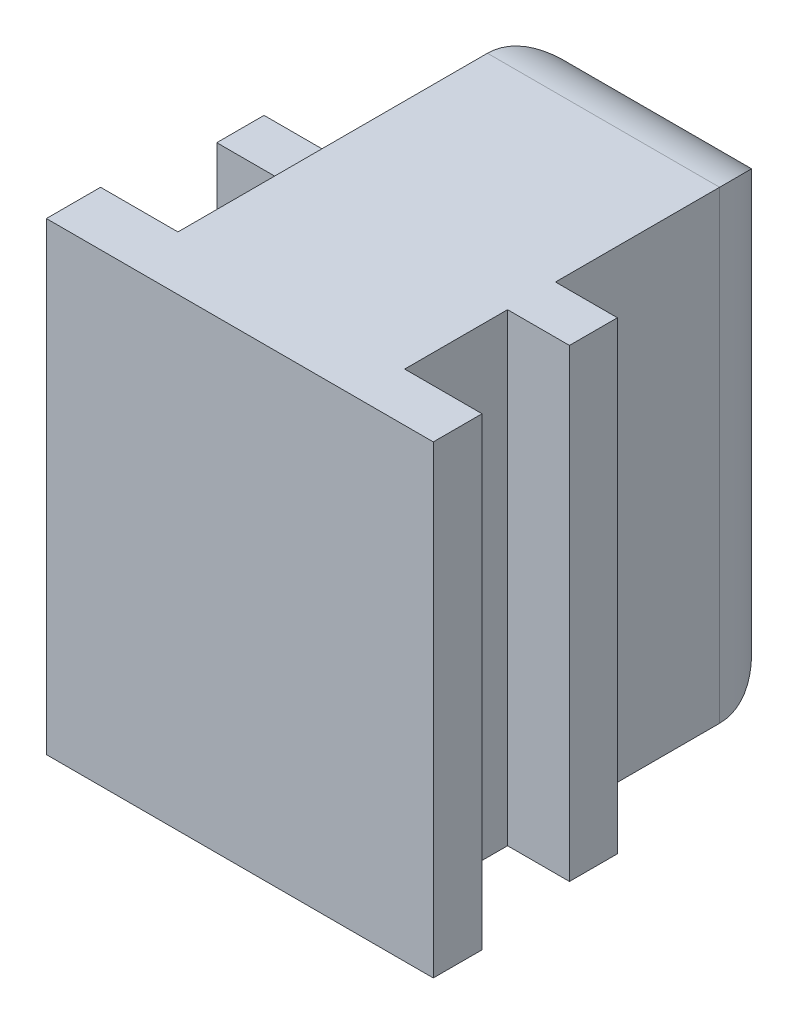
SolidWorks part; units mm, degrees
ref_plane "前视基准面" through (0, 0, 0) normal (0, 0, 1) x (1, 0, 0)
ref_plane "上视基准面" through (0, 0, 0) normal (0, 1, 0) x (1, 0, 0)
ref_plane "右视基准面" through (0, 0, 0) normal (1, 0, 0) x (0, 0, -1)
other "Configuration Table"
sketch "草图3" plane through (0, 0, 0) normal (0, 0, 1) x (1, 0, 0)
  line L1 (-2.0385, 1.183) -> (0.9615, 1.183)
  line L2 (-2.0385, 1.183) -> (-2.0385, -4.817)
  line L3 (-2.0385, -4.817) -> (0.9615, -4.817)
  line L4 (0.9615, 1.183) -> (0.9615, -4.817)
  dimension "D1" = 3
  dimension "D2" = 6
extrude "凸台-拉伸2" add sketch "草图3" along normal blind 3.5
sketch "草图4" plane through (0, 0, 3.5) normal (0, 0, 1) x (1, 0, 0)
  line L1 (-1.2395, -0.1964) -> (0.1779, -0.1964)
  line L2 (-1.2395, -0.1964) -> (-1.2395, -3.2769)
  line L3 (-1.2395, -3.2769) -> (0.1779, -3.2769)
  line L4 (0.1779, -0.1964) -> (0.1779, -3.2769)
extrude "切除-拉伸1" cut sketch "草图4" against normal blind 0.8 flip side to cut
sketch "草图9" plane through (0, 0, 0) normal (0, 0, -1) x (-1, 0, 0)
  line L5 (-0.9615, 1.183) -> (2.0385, 1.183)
  line L6 (-0.9615, 1.183) -> (-0.9615, -4.817)
  line L7 (-0.9615, -4.817) -> (2.0385, -4.817)
  line L8 (2.0385, 1.183) -> (2.0385, -4.817)
extrude "凸台-拉伸5" add sketch "草图9" along normal blind 1.5
fillet "圆角2" radius 1 4 edges at (-0.5385, 1.183, -1.5) (-0.5385, -4.817, -1.5) (-2.0385, -1.817, -1.5) (0.9615, -1.817, -1.5)
ref_plane "基准面1" through (-2.0385, 1.183, -0.5) normal (0, 0, -1) x (-1, 0, 0)
sketch "草图6" plane through (-2.0385, 0, 0) normal (-1, 0, 0) x (0, 0, 1)
  line L0 (2.7, -4.817) -> (-0.5, -4.817) construction
  line L1 (1.587, 1.1312) -> (2.1982, 1.1312)
  line L2 (1.587, 1.1312) -> (1.587, -4.817)
  line L3 (1.587, -4.817) -> (2.1982, -4.817)
  line L4 (2.1982, 1.1312) -> (2.1982, -4.817)
extrude "凸台-拉伸3" add sketch "草图6" along normal blind 0.8
sketch "草图8" plane through (0.9615, 0, 0) normal (1, 0, 0) x (0, 0, -1)
  line L0 (-2.7, 1.183) -> (0.5, 1.183) construction
  line L1 (-2.2402, 1.183) -> (-1.621, 1.183)
  line L2 (-2.2402, 1.183) -> (-2.2402, -4.817)
  line L3 (-2.2402, -4.817) -> (-1.621, -4.817)
  line L4 (-1.621, 1.183) -> (-1.621, -4.817)
  line L5 (-2.7, -4.817) -> (0.5, -4.817) construction
extrude "凸台-拉伸4" add sketch "草图8" along normal blind 0.8
sketch "草图10" plane through (0, 0, 3.5) normal (0, 0, 1) x (1, 0, 0)
  line L1 (-2.0806, 1.0827) -> (0.8643, 1.0827)
  line L2 (-2.0806, 1.0827) -> (-2.0806, -4.852)
  line L3 (-2.0806, -4.852) -> (0.8643, -4.852)
  line L4 (0.8643, 1.0827) -> (0.8643, -4.852)
extrude "凸台-拉伸6" add sketch "草图10" against normal blind 2
sketch "草图11" plane through (0, 0, 2.7) normal (0, 0, 1) x (1, 0, 0)
  line L2 (-2.0385, 1.183) -> (0.9615, 1.183)
  line L3 (-2.0385, 1.183) -> (-2.0385, -4.817)
  line L4 (-2.0385, -4.817) -> (0.9615, -4.817)
  line L5 (0.9615, 1.183) -> (0.9615, -4.817)
extrude "凸台-拉伸7" add sketch "草图11" along normal blind 1.5
sketch "草图12" plane through (-2.0385, 0, 0) normal (-1, 0, 0) x (0, 0, 1)
  line L0 (3.5, -4.817) -> (3.5, 1.0827) construction
  line L1 (4.2, 1.183) -> (3.5, 1.183)
  line L2 (4.2, 1.183) -> (4.2, -4.817)
  line L3 (4.2, -4.817) -> (3.5, -4.817)
  line L4 (3.5, 1.183) -> (3.5, -4.817)
extrude "凸台-拉伸8" add sketch "草图12" along normal blind 1.5
sketch "草图13" plane through (0.9615, 0, 0) normal (1, 0, 0) x (0, 0, -1)
  line L0 (-4.2, -4.817) -> (-2.2402, -4.817) construction
  line L1 (-4.2, 1.183) -> (-3.5697, 1.183)
  line L2 (-4.2, 1.183) -> (-4.2, -4.817)
  line L3 (-4.2, -4.817) -> (-3.5697, -4.817)
  line L4 (-3.5697, 1.183) -> (-3.5697, -4.817)
extrude "凸台-拉伸9" add sketch "草图13" along normal blind 1.5
sketch "草图14" plane through (2.4615, 0, 0) normal (1, 0, 0) x (0, 0, -1)
  line L1 (-4.2, 1.183) -> (-3.5697, 1.183)
  line L2 (-4.2, 1.183) -> (-4.2, -4.817)
  line L3 (-4.2, -4.817) -> (-3.5697, -4.817)
  line L4 (-3.5697, 1.183) -> (-3.5697, -4.817)
extrude "切除-拉伸2" cut sketch "草图14" against normal blind 0.5
sketch "草图15" plane through (-3.5385, 0, 0) normal (-1, 0, 0) x (0, 0, 1)
  line L1 (3.5, 1.183) -> (4.2, 1.183)
  line L2 (3.5, 1.183) -> (3.5, -4.817)
  line L3 (3.5, -4.817) -> (4.2, -4.817)
  line L4 (4.2, 1.183) -> (4.2, -4.817)
extrude "切除-拉伸3" cut sketch "草图15" against normal blind 0.5
sketch "草图16" plane through (0, 1.183, 0) normal (0, 1, 0) x (1, 0, 0)
  line L1 (1.9615, -3.5697) -> (-3.0385, -3.5697)
  line L2 (1.9615, -3.5697) -> (1.9615, -4.2)
  line L3 (1.9615, -4.2) -> (-3.0385, -4.2)
  line L4 (-3.0385, -3.5697) -> (-3.0385, -4.2)
extrude "凸台-拉伸10" add sketch "草图16" along normal blind 1
sketch "草图17" plane through (0, -4.817, 0) normal (0, -1, 0) x (1, 0, 0)
  line L1 (1.9615, 4.2) -> (-3.0385, 4.2)
  line L2 (1.9615, 4.2) -> (1.9615, 3.5)
  line L3 (1.9615, 3.5) -> (-3.0385, 3.5)
  line L4 (-3.0385, 4.2) -> (-3.0385, 3.5)
extrude "凸台-拉伸11" add sketch "草图17" along normal blind 1
sketch "草图18" plane through (0, 2.183, 0) normal (0, 1, 0) x (1, 0, 0)
  line L0 (1.9615, -3.5697) -> (-3.0385, -3.5697) construction
  line L1 (1.9615, -3.5697) -> (-3.0385, -3.5697)
  line L2 (1.9615, -3.5697) -> (1.9615, -4.2)
  line L3 (1.9615, -4.2) -> (-3.0385, -4.2)
  line L4 (-3.0385, -3.5697) -> (-3.0385, -4.2)
  line L5 (1.9615, -4.2) -> (1.9615, -3.5697) construction
extrude "切除-拉伸4" cut sketch "草图18" against normal blind 1
sketch "草图19" plane through (0, -5.817, 0) normal (0, -1, 0) x (1, 0, 0)
  line L1 (-3.0385, 4.2) -> (1.9615, 4.2)
  line L2 (-3.0385, 4.2) -> (-3.0385, 3.5)
  line L3 (-3.0385, 3.5) -> (1.9615, 3.5)
  line L4 (1.9615, 4.2) -> (1.9615, 3.5)
extrude "切除-拉伸5" cut sketch "草图19" against normal blind 1
